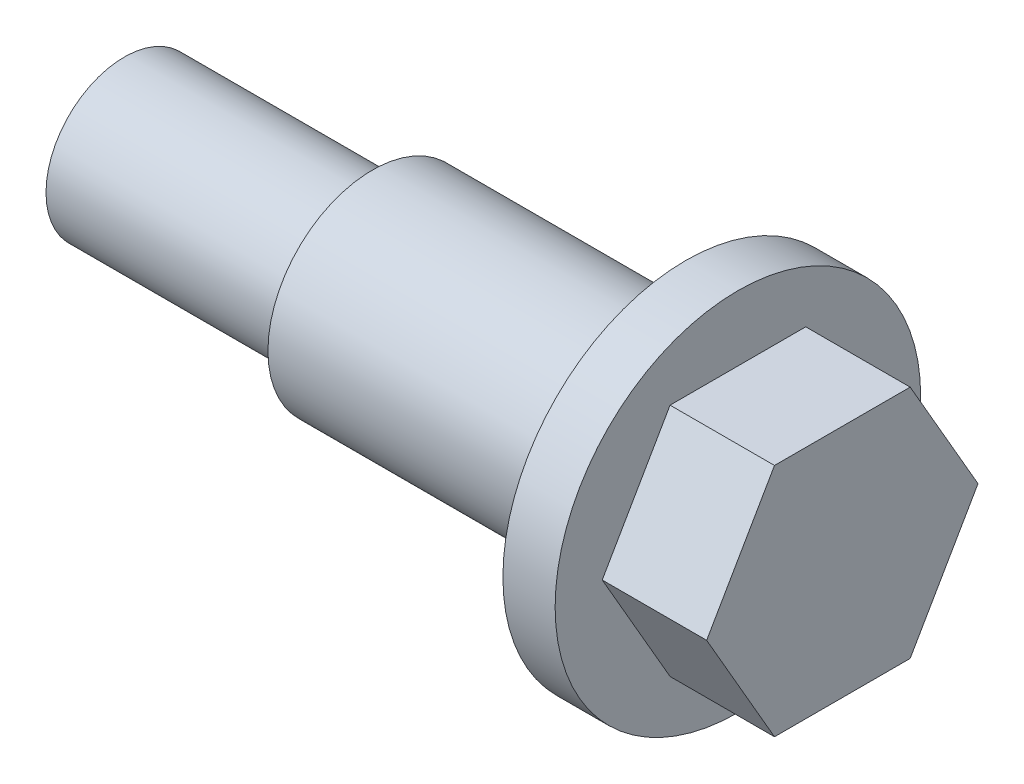
SolidWorks part; units mm, degrees
ref_plane "Front Plane" through (0, 0, 0) normal (0, 0, 1) x (1, 0, 0)
ref_plane "Top Plane" through (0, 0, 0) normal (0, 1, 0) x (1, 0, 0)
ref_plane "Right Plane" through (0, 0, 0) normal (1, 0, 0) x (0, 0, -1)
sketch "Sketch1" plane through (0, 0, 0) normal (0, 0, 1) x (1, 0, 0)
  line L0 (0, 0) -> (27.5, 0) construction
  line L1 (0, 0) -> (0, 3)
  line L2 (0, 3) -> (9.5, 3)
  line L3 (9.5, 3) -> (9.5, 4)
  line L4 (9.5, 4) -> (21.5, 4)
  line L5 (21.5, 4) -> (21.5, 7)
  line L6 (21.5, 7) -> (23.5, 7)
  line L7 (23.5, 7) -> (23.5, 4.5)
  line L8 (23.5, 4.5) -> (27.5, 4.5)
  line L9 (27.5, 4.5) -> (27.5, 0)
  line L10 (0, 0) -> (27.5, 0)
  dimension "D1" = 27.5
  dimension "D2" = 3
  dimension "D3" = 9.5
  dimension "D4" = 8
  dimension "D5" = 12
  dimension "D6" = 2
  dimension "D7" = 4
  dimension "D8" = 14
  dimension "D9" = 9
revolve "Revolve1" add sketch "Sketch1" angle 360 about L0
sketch "Sketch2" plane through (27.5, 0, 0) normal (1, 0, 0) x (0, 0, -1)
  line L1 (-2.5981, 4.5) -> (-5.1962, 0)
  line L2 (-5.1962, 0) -> (-2.5981, -4.5)
  line L3 (-2.5981, -4.5) -> (2.5981, -4.5)
  line L4 (2.5981, -4.5) -> (5.1962, 0)
  line L5 (5.1962, 0) -> (2.5981, 4.5)
  line L6 (2.5981, 4.5) -> (-2.5981, 4.5)
  circle A0 centre (0, 0) radius 4.5 construction
  dimension "D1" = 9
extrude "Boss-Extrude1" add sketch "Sketch2" against normal up to surface (4 mm away) up to face at (23.5, 0, 7)
